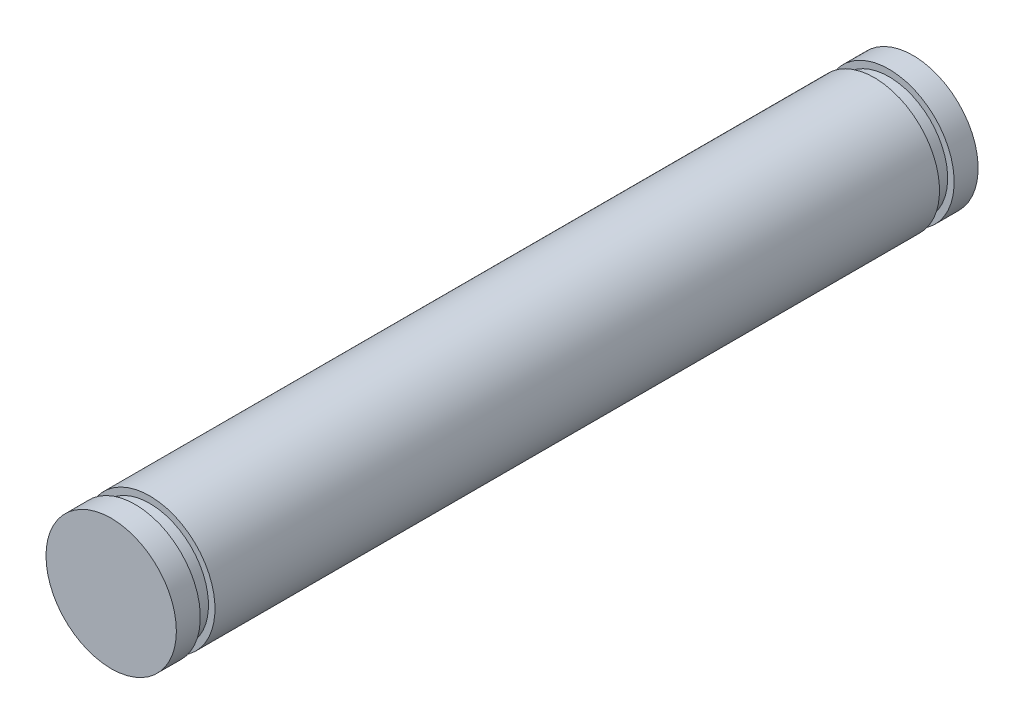
SolidWorks part; units mm, degrees
ref_plane "Front Plane" through (0, 0, 0) normal (0, 0, 1) x (1, 0, 0)
ref_plane "Top Plane" through (0, 0, 0) normal (0, 1, 0) x (1, 0, 0)
ref_plane "Right Plane" through (0, 0, 0) normal (1, 0, 0) x (0, 0, -1)
sketch "Sketch1" plane through (0, 0, 0) normal (0, 0, 1) x (1, 0, 0)
  line L0 (-4, 0) -> (4, 0) construction
  line L5 (0, 4) -> (0, -4) construction
  circle A1 centre (0, 0) radius 4
  point P7 (-4, 0)
  point P8 (4, 0)
  point P12 (0, -4)
  point P13 (0, 4)
  dimension "Diameter" = 8
sketch "Sketch2" plane through (0, 0, 0) normal (1, 0, 0) x (0, 0, -1)
  line L0 (-42, -4) -> (-42, 4) construction
  line L1 (50, -4) -> (-50, -4)
  line L2 (50, -4) -> (50, 4)
  line L3 (50, 4) -> (-50, 4)
  line L4 (-50, -4) -> (-50, 4)
  line L5 (50, -4) -> (-50, 4) construction
  line L6 (50, 4) -> (-50, -4) construction
  line L7 (42, -4) -> (42, 4) construction
  line L8 (-50, 3.44) -> (-49.44, 4) construction
  point P0 (0, 0)
  point P8 (-50, 4)
  point P9 (50, 4)
  point P14 (-42, 4)
  point P15 (-42, -4)
  point P16 (42, 4)
  point P17 (42, -4)
  point P25 (0, -4)
  dimension "Length" = 100
  dimension "D1" = 8
  dimension "D2" = 8
  dimension "Chamfer Typ," = 45
  dimension "D4" = 0.56
sketch "Sketch3" plane through (0, 0, 0) normal (0, 0, 1) x (1, 0, 0)
  circle A0 centre (0, 0) radius 4 construction
  circle A1 centre (0, 0) radius 4
extrude "Boss-Extrude1" add sketch "Sketch3" along normal up to vertex (50 mm away) and the other way up to vertex (50 mm away) up to point (0, 4, 50) other way up to point (0, 4, -50)
chamfer "Chamfer1" distance 0.56 angle 45 2 edges at (4, 0, -50) (4, 0, 50)
sketch "Sketch4" plane through (0, 0, 50) normal (0, 0, 1) x (1, 0, 0)
  circle A0 centre (0, 0) radius 8.463
extrude "Cut-Extrude1" cut sketch "Sketch4" against normal blind 25.4
sketch "Sketch5" plane through (0, 0, -50) normal (0, 0, -1) x (-1, 0, 0)
  circle A0 centre (0, 0) radius 6.6298
extrude "Cut-Extrude2" cut sketch "Sketch5" against normal blind 25.4
sketch "Sketch6" plane through (0, 0, -24.6) normal (0, 0, -1) x (-1, 0, 0)
  circle A0 centre (0, 0) radius 4
  circle A1 centre (0, 0) radius 3.6
  circle A2 centre (0, 0) radius 4 construction
  dimension "D1" = 0.4
extrude "Cut-Extrude3" cut sketch "Sketch6" along normal blind 0.9 from offset 2.37 offset against normal yes
ref_plane "Plane1" through (0, 0, 0) normal (0, 0, -1) x (-1, 0, 0)
mirror "Mirror1" about plane through (0, 0, 0) normal (0, 0, -1) of "Cut-Extrude3"
equation "\"D1@Sketch2\"=\"Diameter@Sketch1\""
equation "\"D2@Sketch2\"=\"Diameter@Sketch1\""
equation "\"D1@Chamfer1\"=\"Diameter@Sketch1\"*.07"
equation "\"D4@Sketch2\"=\"Diameter@Sketch1\"*.07"
equation "\"D2@Chamfer1\"=\"Chamfer Typ,@Sketch2\""
